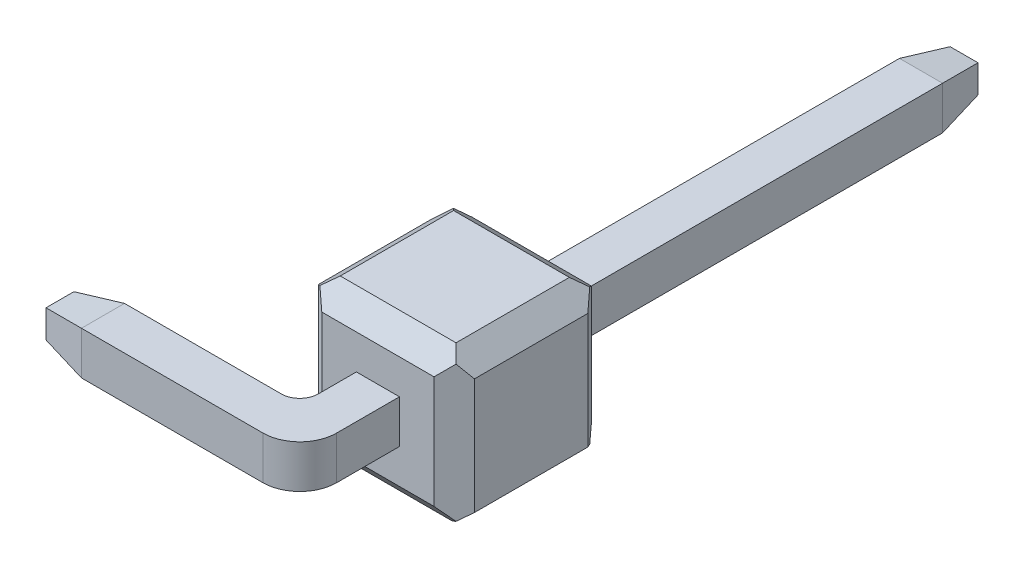
SolidWorks part; units mm, degrees
ref_plane "Front" through (0, 0, 0) normal (0, 0, 1) x (1, 0, 0)
ref_plane "Top" through (0, 0, 0) normal (0, 1, 0) x (1, 0, 0)
ref_plane "Right" through (0, 0, 0) normal (1, 0, 0) x (0, 0, -1)
sketch "Эскиз1" plane through (0, 0, 0) normal (0, 1, 0) x (1, 0, 0)
  line L0 (0, 0) -> (0, -10.8) construction
  line L1 (0, -10.8) -> (-3.9, -10.8) construction
  line L2 (0.35, 0) -> (0.35, -10.55)
  line L3 (-0.25, -11.15) -> (-3.9, -11.15)
  line L4 (-0.35, 0) -> (-0.35, -10.15)
  line L5 (-0.65, -10.45) -> (-3.9, -10.45)
  line L6 (-0.35, 0) -> (0.35, 0)
  line L7 (-3.9, -10.45) -> (-3.9, -11.15)
  line L8 (0.35, 0) -> (0.35, -11.15) construction
  line L9 (0.35, -11.15) -> (-3.9, -11.15) construction
  line L10 (-0.35, 0) -> (-0.35, -10.45) construction
  line L11 (-0.35, -10.45) -> (-3.9, -10.45) construction
  arc A1 (-0.35, -10.15) -> (-0.65, -10.45) centre (-0.65, -10.15) cw
  arc A2 (0.35, -10.55) -> (-0.25, -11.15) centre (-0.25, -10.55) cw
  dimension "D4" = 0.6
  dimension "D1" = 0.35
  dimension "D2" = 0.35
extrude "Бобышка-Вытянуть1" add sketch "Эскиз1" along normal blind 0.7
chamfer "Фаска1" distance 0.7 angle 10 4 edges at (0.35, 0.35, 0) (0, 0, 0) (-0.35, 0.35, 0) (0, 0.7, 0)
chamfer "Фаска2" distance 0.7 angle 10 4 edges at (-3.9, 0.35, 10.45) (-3.9, 0, 10.8) (-3.9, 0.35, 11.15) (-3.9, 0.7, 10.8)
ref_plane "Плоскость1" through (0, 0, 9.53) normal (0, 0, 1) x (1, 0, 0)
sketch "Эскиз2" plane through (0, 0, 9.53) normal (0, 0, 1) x (1, 0, 0)
  line L0 (-3.9, 0.35) -> (-0.6, 0.35) construction
  line L1 (-3.9, 0.5766) -> (-3.9, 0.1234) construction
  line L2 (-0.6, 0.35) -> (0, 0.35) construction
  line L4 (1.27, -0.92) -> (-1.27, -0.92)
  line L5 (1.27, -0.92) -> (1.27, 1.62)
  line L6 (1.27, 1.62) -> (-1.27, 1.62)
  line L7 (-1.27, -0.92) -> (-1.27, 1.62)
  line L8 (1.27, -0.92) -> (-1.27, 1.62) construction
  line L9 (1.27, 1.62) -> (-1.27, -0.92) construction
extrude "Бобышка-Вытянуть2" add sketch "Эскиз2" against normal blind 2.5
chamfer "Фаска3" distance 0.3 angle 50 4 edges at (0, -0.92, 7.03) (-1.27, 0.35, 7.03) (0, 1.62, 7.03) (1.27, 0.35, 7.03)
chamfer "Фаска4" distance 0.3 angle 50 4 edges at (0, -0.92, 9.53) (-1.27, 0.35, 9.53) (0, 1.62, 9.53) (1.27, 0.35, 9.53)
chamfer "Фаска5" distance 0.3 angle 50 4 edges at (1.27, 1.62, 8.3088) (-1.27, 1.62, 8.3088) (-1.27, -0.92, 8.3088) (1.27, -0.92, 8.3088)
